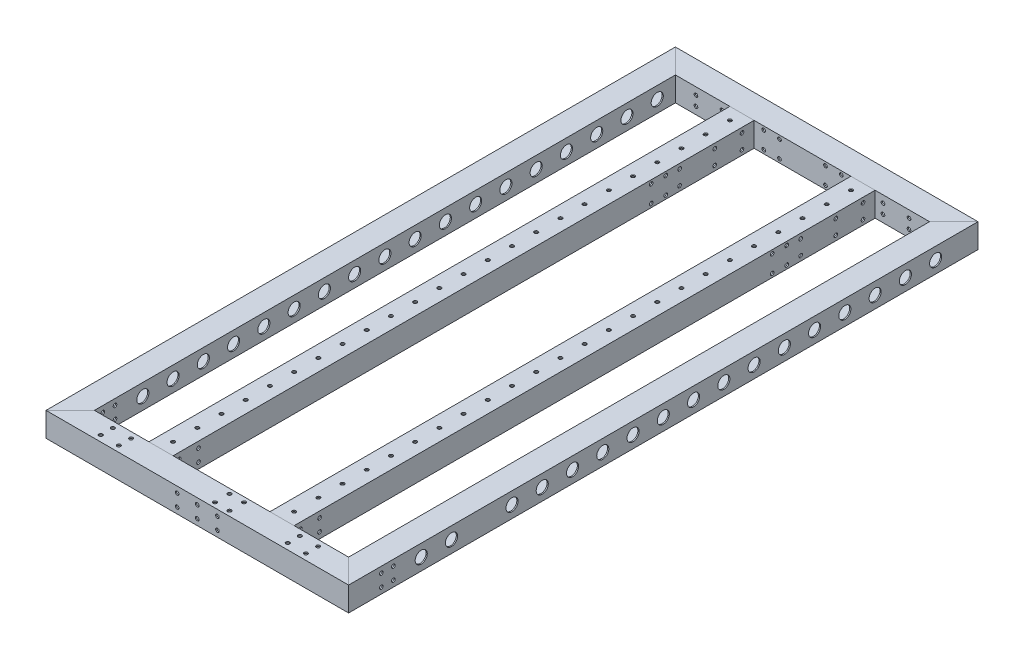
SolidWorks part; units mm, degrees
material "7050-T73510"
ref_plane "前视基准面" through (0, 0, 0) normal (0, 0, 1) x (1, 0, 0)
ref_plane "上视基准面" through (0, 0, 0) normal (0, 1, 0) x (1, 0, 0)
ref_plane "右视基准面" through (0, 0, 0) normal (1, 0, 0) x (0, 0, -1)
sketch "草图1" plane through (0, 0, 0) normal (0, 1, 0) x (1, 0, 0)
  line L0 (-50, 250) -> (-50, -250)
  line L1 (-115, -250) -> (115, -250)
  line L2 (-115, -250) -> (-115, 250)
  line L3 (-115, 250) -> (115, 250)
  line L4 (115, -250) -> (115, 250)
  line L5 (-115, -250) -> (115, 250) construction
  line L6 (-115, 250) -> (115, -250) construction
  line L7 (0, 250) -> (0, -250) construction
  line L8 (50, 250) -> (50, -250)
  point P0 (0, 0)
  dimension "D1" = 500
  dimension "D2" = 230
  dimension "D3" = 50
other "Wl 20X20X1(1)"
ref_plane "基准面1" through (-115, 0, -250) normal (1, 0, 0) x (0, 0, -1)
sketch "草图11" plane through (-115, 0, -250) normal (1, 0, 0) x (0, 0, -1)
  line L8 (-9, -9) -> (9, -9)
  line L9 (-10, -10) -> (10, -10)
  line L10 (-10, -10) -> (-10, 10)
  line L11 (-10, 10) -> (10, 10)
  line L12 (10, -10) -> (10, 10)
  line L13 (9, -9) -> (9, 9)
  line L14 (-9, 9) -> (9, 9)
  line L15 (-9, -9) -> (-9, 9)
  point P4 (0, 0)
  dimension "D1" = 20
  dimension "D2" = 20
ref_plane "基准面2" through (0, 0, 0) normal (0, 1, 0) x (1, 0, 0)
sketch "草图12" plane through (0, 0, 0) normal (0, 1, 0) x (1, 0, 0)
  line L0 (-40, -140) -> (40, -140)
  line L1 (-40, -240) -> (-40, 240) construction
  line L2 (40, -240) -> (40, 240) construction
  line L3 (-105, -240) -> (105, -240) construction
  dimension "D1" = 100
sketch "草图14" plane through (0, 10, 0) normal (0, 1, 0) x (1, 0, 0)
  line L0 (105, 240) -> (-105, 240) construction
  line L1 (-40, -240) -> (-40, 240) construction
  line L2 (0, 240) -> (0, -240) construction
  line L3 (-105, -240) -> (105, -240) construction
  circle A0 centre (-50, 230) radius 1.5
  circle A1 centre (50, 230) radius 1.5
  circle A2 centre (-50, 210) radius 1.5
  circle A3 centre (50, 210) radius 1.5
  circle A4 centre (-50, 190) radius 1.5
  circle A5 centre (50, 190) radius 1.5
  circle A6 centre (-50, 170) radius 1.5
  circle A7 centre (50, 170) radius 1.5
  circle A8 centre (-50, 150) radius 1.5
  circle A9 centre (50, 150) radius 1.5
  circle A10 centre (-50, 130) radius 1.5
  circle A11 centre (50, 130) radius 1.5
  circle A12 centre (-50, 110) radius 1.5
  circle A13 centre (50, 110) radius 1.5
  circle A14 centre (-50, 90) radius 1.5
  circle A15 centre (50, 90) radius 1.5
  circle A16 centre (-50, 70) radius 1.5
  circle A17 centre (50, 70) radius 1.5
  circle A18 centre (-50, 50) radius 1.5
  circle A19 centre (50, 50) radius 1.5
  circle A20 centre (-50, 30) radius 1.5
  circle A21 centre (50, 30) radius 1.5
  circle A22 centre (-50, 10) radius 1.5
  circle A23 centre (50, 10) radius 1.5
  circle A24 centre (-50, -10) radius 1.5
  circle A25 centre (50, -10) radius 1.5
  circle A26 centre (-50, -30) radius 1.5
  circle A27 centre (50, -30) radius 1.5
  circle A28 centre (-50, -50) radius 1.5
  circle A29 centre (50, -50) radius 1.5
  circle A30 centre (-50, -70) radius 1.5
  circle A31 centre (50, -70) radius 1.5
  circle A32 centre (-50, -90) radius 1.5
  circle A33 centre (50, -90) radius 1.5
  circle A34 centre (-50, -110) radius 1.5
  circle A35 centre (50, -110) radius 1.5
  circle A36 centre (-50, -130) radius 1.5
  circle A37 centre (50, -130) radius 1.5
  circle A38 centre (-50, -150) radius 1.5
  circle A39 centre (50, -150) radius 1.5
  circle A40 centre (-50, -170) radius 1.5
  circle A41 centre (50, -170) radius 1.5
  circle A42 centre (-50, -190) radius 1.5
  circle A43 centre (50, -190) radius 1.5
  circle A44 centre (-50, -210) radius 1.5
  circle A45 centre (50, -210) radius 1.5
  circle A46 centre (-50, -230) radius 1.5
  circle A47 centre (50, -230) radius 1.5
  dimension "D2" = 3
  dimension "D3" = 10
  dimension "D1" = 10
  dimension "D4" = 24
extrude "切除-拉伸2" cut sketch "草图14" against normal blind 20
extrude "切除-拉伸3" cut sketch "草图15" against normal blind 20
sketch "草图15" plane through (51.2492, -42.8186, -240) normal (0, 0, 1) x (1, 0, 0)
  circle A8 centre (15.2508, 38.8186) radius 1.5
  circle A9 centre (15.2508, 46.8186) radius 1.5
  circle A10 centre (36.7508, 46.8186) radius 1.5
  circle A11 centre (36.7508, 38.8186) radius 1.5
  circle A12 centre (-139.2492, 38.8186) radius 1.5
  circle A13 centre (-139.2492, 46.8186) radius 1.5
  circle A14 centre (-117.7492, 38.8186) radius 1.5
  circle A15 centre (-117.7492, 46.8186) radius 1.5
  circle A24 centre (-70.2492, 35.8186) radius 1.5
  circle A25 centre (-70.2492, 49.8186) radius 1.5
  circle A26 centre (-83.2492, 35.8186) radius 1.5
  circle A27 centre (-83.2492, 49.8186) radius 1.5
  circle A28 centre (-32.2492, 49.8186) radius 1.5
  circle A29 centre (-32.2492, 35.8186) radius 1.5
  circle A30 centre (-19.2492, 35.8186) radius 1.5
  circle A31 centre (-19.2492, 49.8186) radius 1.5
extrude "切除-拉伸4" [suppressed] cut sketch "草图16" against normal blind 20
sketch "草图16" plane through (51.2492, 10, 0) normal (0, 1, 0) x (1, 0, 0)
  circle A0 centre (-1.2492, 250) radius 1.5
  circle A1 centre (-101.2492, 250) radius 1.5
  circle A14 centre (-19.2492, -256) radius 1.5
  circle A15 centre (-31.2492, -256) radius 1.5
  circle A16 centre (-19.2492, -244) radius 1.5
  circle A17 centre (-31.2492, -244) radius 1.5
  circle A18 centre (-120.9992, -245) radius 1.5
  circle A19 centre (-120.9992, -255) radius 1.5
  circle A20 centre (-135.9992, -245) radius 1.5
  circle A21 centre (-135.9992, -255) radius 1.5
  circle A22 centre (18.5008, -255) radius 1.5
  circle A23 centre (18.5008, -245) radius 1.5
  circle A24 centre (33.5008, -255) radius 1.5
  circle A25 centre (33.5008, -245) radius 1.5
extrude "切除-拉伸5" [suppressed] cut sketch "草图17" against normal blind 20
sketch "草图17" plane through (51.2492, -42.8186, 240) normal (0, 0, -1) x (-1, 0, 0)
  circle A2 centre (25.2492, 37.819) radius 1.5
  circle A3 centre (25.2492, 47.819) radius 1.5
sketch "草图19" plane through (-125, 0, 0) normal (-1, 0, 0) x (0, 0, 1)
  line L0 (260, 10) -> (260, -10) construction
  line L1 (223, 5) -> (233, 5) construction
  line L2 (223, 5) -> (223, -5) construction
  line L3 (223, -5) -> (233, -5) construction
  line L4 (233, 5) -> (233, -5) construction
  circle A0 centre (223, 5) radius 1.5
  circle A1 centre (223, -5) radius 1.5
  circle A2 centre (233, -5) radius 1.5
  circle A3 centre (233, 5) radius 1.5
  dimension "D1" = 3
  dimension "D2" = 27
extrude "切除-拉伸7" cut sketch "草图19" against normal blind 20
sketch "草图20" plane through (125, 0, 0) normal (1, 0, 0) x (0, 0, -1)
  line L0 (-260, 10) -> (-260, -10) construction
  line L1 (-233, 5) -> (-223, 5) construction
  line L2 (-233, 5) -> (-233, -5) construction
  line L3 (-233, -5) -> (-223, -5) construction
  line L4 (-223, 5) -> (-223, -5) construction
  circle A0 centre (-233, 5) radius 1.5
  circle A1 centre (-223, 5) radius 1.5
  circle A2 centre (-223, -5) radius 1.5
  circle A3 centre (-233, -5) radius 1.5
  dimension "D1" = 27
extrude "切除-拉伸8" cut sketch "草图20" against normal blind 20
sketch "草图22" plane through (60, 0, 0) normal (1, 0, 0) x (0, 0, -1)
  circle A0 centre (-219, -5) radius 1.5
  circle A1 centre (-219, 5) radius 1.5
  circle A2 centre (-235, 5) radius 1.5
  circle A3 centre (-235, -5) radius 1.5
  dimension "D1" = 3
  dimension "D2" = 3
extrude "切除-拉伸9" cut sketch "草图22" against normal up to surface (120 mm away)
sketch "草图23" plane through (0, 0, 260) normal (0, 0, 1) x (1, 0, 0)
  line L0 (-40, 0) -> (40, 0) construction
  line L1 (-40, -10) -> (-40, 10) construction
  line L2 (40, 10) -> (40, -10) construction
  line L3 (0, 10) -> (0, -10) construction
  line L4 (-125, 10) -> (125, 10) construction
  line L5 (-125, -10) -> (125, -10) construction
  line L7 (-16.6, -5) -> (16.6, -5) construction
  line L8 (-16.6, -5) -> (-16.6, 5) construction
  line L9 (-16.6, 5) -> (16.6, 5) construction
  line L10 (16.6, -5) -> (16.6, 5) construction
  line L11 (-16.6, -5) -> (16.6, 5) construction
  line L12 (-16.6, 5) -> (16.6, -5) construction
  circle A4 centre (-16.6, 5) radius 1.5
  circle A5 centre (16.6, 5) radius 1.5
  circle A6 centre (-16.6, -5) radius 1.5
  circle A7 centre (16.6, -5) radius 1.5
  circle A8 centre (0, 5) radius 1.5
  circle A9 centre (0, -5) radius 1.5
  point P20 (0, 0)
  dimension "D1" = 10
  dimension "D3" = 3
  dimension "D4" = 3
  dimension "D5" = 3
  dimension "D2" = 33.2
extrude "切除-拉伸10" cut sketch "草图23" against normal blind 20
sketch "草图24" plane through (60, 0, 0) normal (1, 0, 0) x (0, 0, -1)
  line L0 (260, 0) -> (-260, 0) construction
  line L1 (260, -10) -> (260, 10) construction
  line L2 (-260, 10) -> (-260, -10) construction
  line L4 (155, -7) -> (167, -7) construction
  line L5 (155, -7) -> (155, 7) construction
  line L6 (155, 7) -> (167, 7) construction
  line L7 (167, -7) -> (167, 7) construction
  line L8 (155, -7) -> (167, 7) construction
  line L9 (155, 7) -> (167, -7) construction
  circle A0 centre (155, 7) radius 1.5
  circle A1 centre (167, 7) radius 1.5
  circle A2 centre (155, -7) radius 1.5
  circle A3 centre (167, -7) radius 1.5
  point P6 (161, 0)
  dimension "D4" = 3
  dimension "D5" = 3
  dimension "D1" = 93
  dimension "D2" = 12
  dimension "D3" = 14
extrude "切除-拉伸11" cut sketch "草图24" against normal blind 130
extrude "切除-拉伸12" cut sketch "草图25" against normal blind 20 and the other way blind 100
sketch "草图25" plane through (40, -42.8186, 0) normal (-1, 0, 0) x (0, 0, 1)
  circle A6 centre (-178.5, 36.8186) radius 1.5
  circle A7 centre (-178.5, 48.8186) radius 1.5
  circle A8 centre (-230, 36.8186) radius 1.5
  circle A9 centre (-230, 48.8186) radius 1.5
  circle A10 centre (-207.5, 36.8186) radius 1.5
  circle A11 centre (-207.5, 48.8186) radius 1.5
sketch "草图26" plane through (0, 10, 0) normal (0, 1, 0) x (1, 0, 0)
  line L0 (-115, -250) -> (115, -250) construction
  line L1 (-125, -260) -> (-105, -240) construction
  line L2 (125, -260) -> (105, -240) construction
  line L3 (40, -240) -> (40, 240) construction
  line L4 (10.6, -256) -> (22.6, -256) construction
  line L5 (10.6, -256) -> (10.6, -244) construction
  line L6 (10.6, -244) -> (22.6, -244) construction
  line L7 (22.6, -256) -> (22.6, -244) construction
  line L8 (10.6, -256) -> (22.6, -244) construction
  line L9 (10.6, -244) -> (22.6, -256) construction
  circle A0 centre (10.6, -244) radius 1.5
  circle A1 centre (22.6, -244) radius 1.5
  circle A2 centre (10.6, -256) radius 1.5
  circle A3 centre (22.6, -256) radius 1.5
  point P6 (16.6, -250)
  dimension "D4" = 3
  dimension "D5" = 3
  dimension "D1" = 17.4
  dimension "D2" = 12
  dimension "D3" = 12
extrude "切除-拉伸13" cut sketch "草图26" against normal through all
sketch "草图28" plane through (125, 0, 0) normal (1, 0, 0) x (0, 0, -1)
  line L0 (-260, 0) -> (260, 0) construction
  line L1 (-260, 10) -> (-260, -10) construction
  line L2 (260, -10) -> (260, 10) construction
  line L3 (0, -10) -> (0, 10) construction
  line L4 (-260, 10) -> (260, 10) construction
  line L5 (-260, -10) -> (260, -10) construction
  circle A0 centre (0, 0) radius 5
  circle A1 centre (25, 0) radius 5
  circle A2 centre (50, 0) radius 5
  circle A3 centre (75, 0) radius 5
  circle A4 centre (100, 0) radius 5
  circle A5 centre (125, 0) radius 5
  circle A6 centre (150, 0) radius 5
  circle A7 centre (175, 0) radius 5
  circle A8 centre (200, 0) radius 5
  circle A9 centre (225, 0) radius 5
  circle A10 centre (-225, 0) radius 5 construction
  circle A11 centre (-200, 0) radius 5
  circle A12 centre (-175, 0) radius 5
  circle A13 centre (-150, 0) radius 5 construction
  circle A14 centre (-125, 0) radius 5
  circle A15 centre (-100, 0) radius 5
  circle A16 centre (-75, 0) radius 5
  circle A17 centre (-50, 0) radius 5
  circle A18 centre (-25, 0) radius 5
  dimension "D1" = 10
extrude "切除-拉伸15" cut sketch "草图28" against normal blind 20
sketch "草图29" plane through (-125, 0, 0) normal (-1, 0, 0) x (0, 0, 1)
  line L0 (-260, 0) -> (260, 0) construction
  line L1 (-260, 10) -> (-260, -10) construction
  line L2 (260, -10) -> (260, 10) construction
  line L3 (0, -10) -> (0, 10) construction
  line L4 (-260, -10) -> (260, -10) construction
  line L5 (-260, 10) -> (260, 10) construction
  circle A0 centre (0, 0) radius 5
  circle A1 centre (25, 0) radius 5
  circle A2 centre (50, 0) radius 5
  circle A3 centre (75, 0) radius 5
  circle A4 centre (100, 0) radius 5
  circle A5 centre (125, 0) radius 5
  circle A6 centre (150, 0) radius 5
  circle A7 centre (175, 0) radius 5
  circle A8 centre (200, 0) radius 5
  circle A9 centre (225, 0) radius 5 construction
  circle A10 centre (-225, 0) radius 5
  circle A11 centre (-200, 0) radius 5
  circle A12 centre (-175, 0) radius 5
  circle A13 centre (-150, 0) radius 5
  circle A14 centre (-125, 0) radius 5
  circle A15 centre (-100, 0) radius 5
  circle A16 centre (-75, 0) radius 5
  circle A17 centre (-50, 0) radius 5
  circle A18 centre (-25, 0) radius 5
  dimension "D1" = 10
  dimension "D2" = 10
extrude "切除-拉伸16" cut sketch "草图29" against normal blind 20
sketch "草图30" plane through (0, 10, 0) normal (0, 1, 0) x (1, 0, 0)
  line L0 (-115, -250) -> (115, -250) construction
  line L1 (-125, -260) -> (-105, -240) construction
  line L2 (125, -260) -> (105, -240) construction
  line L3 (125, -260) -> (125, 260) construction
  line L4 (69.75, -255) -> (84.75, -255) construction
  line L5 (69.75, -255) -> (69.75, -245) construction
  line L6 (69.75, -245) -> (84.75, -245) construction
  line L7 (84.75, -255) -> (84.75, -245) construction
  line L8 (69.75, -255) -> (84.75, -245) construction
  line L9 (69.75, -245) -> (84.75, -255) construction
  line L10 (0, -240) -> (0, -260) construction
  line L11 (-105, -240) -> (105, -240) construction
  line L12 (-125, -260) -> (125, -260) construction
  line L13 (-69.75, -245) -> (-84.75, -255) construction
  line L14 (-69.75, -255) -> (-84.75, -245) construction
  line L15 (-84.75, -255) -> (-84.75, -245) construction
  line L16 (-69.75, -245) -> (-84.75, -245) construction
  line L17 (-69.75, -255) -> (-69.75, -245) construction
  line L18 (-69.75, -255) -> (-84.75, -255) construction
  circle A0 centre (69.75, -245) radius 1.5
  circle A1 centre (84.75, -245) radius 1.5
  circle A2 centre (84.75, -255) radius 1.5
  circle A3 centre (69.75, -255) radius 1.5
  circle A4 centre (-69.75, -255) radius 1.5
  circle A5 centre (-84.75, -255) radius 1.5
  circle A6 centre (-84.75, -245) radius 1.5
  circle A7 centre (-69.75, -245) radius 1.5
  point P6 (77.25, -250)
  point P31 (-77.25, -250)
  dimension "D4" = 3
  dimension "D5" = 3
  dimension "D1" = 10
  dimension "D2" = 15
  dimension "D3" = 40.25
extrude "切除-拉伸17" cut sketch "草图30" against normal through all
